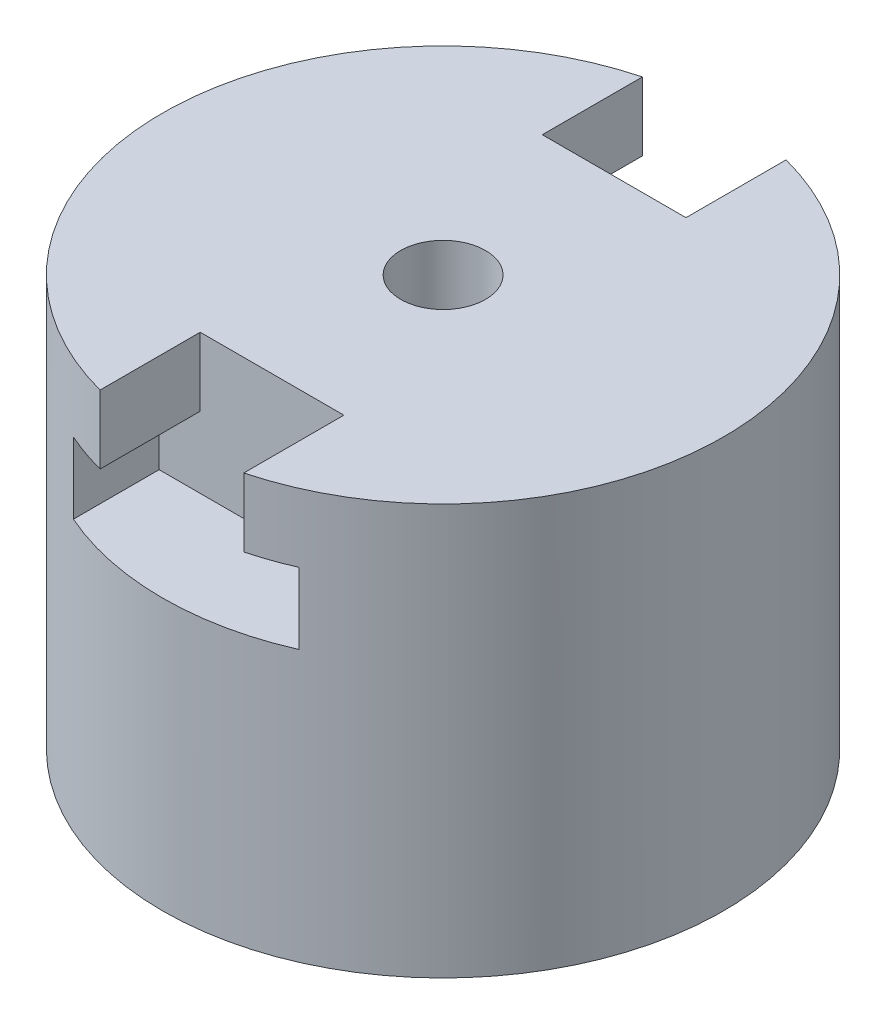
SolidWorks part; units mm, degrees
ref_plane "Front Plane" through (0, 0, 0) normal (0, 0, 1) x (1, 0, 0)
ref_plane "Top Plane" through (0, 0, 0) normal (0, 1, 0) x (1, 0, 0)
ref_plane "Right Plane" through (0, 0, 0) normal (1, 0, 0) x (0, 0, -1)
sketch "Sketch2" plane through (0, 0, 0) normal (0, 1, 0) x (1, 0, 0)
  circle A0 centre (0, 0) radius 20.5
  dimension "D1" = 41
extrude "Boss-Extrude2" add sketch "Sketch2" along normal blind 30
sketch "Sketch3" plane through (0, 0, 0) normal (0, -1, 0) x (1, 0, 0)
  circle A0 centre (0, 0) radius 11.5
sketch "Sketch4" plane through (0, 0, 0) normal (0, -1, 0) x (1, 0, 0)
  circle A0 centre (0, 0) radius 12
  circle A1 centre (0, 0) radius 15.5
  dimension "D1" = 24
  dimension "D2" = 31
extrude "Cut-Extrude2" cut sketch "Sketch4" against normal blind 5
sketch "Sketch5" plane through (0, 0, 0) normal (0, 0, 1) x (1, 0, 0)
  line L0 (0, 0) -> (0, 11.4472)
  line L1 (0, 11.4472) -> (3.1, 11.4472)
  line L2 (3.1, 11.4472) -> (11.5, 0)
  line L3 (-11.5, 0) -> (11.5, 0) construction
  line L4 (11.5, 0) -> (0, 0)
  dimension "D1" = 3.1
revolve "Cut-Revolve1" cut sketch "Sketch5" angle 360 about L0
sketch "Sketch6" plane through (0, 11.4472, 0) normal (0, -1, 0) x (1, 0, 0)
  circle A0 centre (0, 0) radius 3.1
extrude "Cut-Extrude3" cut sketch "Sketch6" against normal through all
ref_plane "Plane2" through (0, 0, 20.5) normal (0, 0, 1) x (1, 0, 0)
sketch "Sketch8" plane through (0, 0, 20.5) normal (0, 0, 1) x (1, 0, 0)
  line L5 (-5.25, 30) -> (5.25, 30)
  line L6 (-8.25, 25) -> (-8.25, 19.8)
  line L7 (-8.25, 19.8) -> (8.25, 19.8)
  line L8 (8.25, 25) -> (8.25, 19.8)
  line L9 (0, 30) -> (0, 0) construction
  line L13 (-8.25, 25) -> (-5.25, 25)
  line L14 (-5.25, 30) -> (-5.25, 25)
  line L17 (8.25, 25) -> (5.25, 25)
  line L18 (5.25, 30) -> (5.25, 25)
  dimension "D1" = 16.5
  dimension "D3" = 8.25
  dimension "D4" = 3
  dimension "5" = 3
  dimension "D5" = 5
  dimension "D6" = 5
extrude "Cut-Extrude4" cut sketch "Sketch8" against normal blind 8
ref_plane "Plane3" through (0, 0, -20.5) normal (0, 0, 1) x (1, 0, 0)
sketch "Sketch9" plane through (0, 0, -20.5) normal (0, 0, 1) x (1, 0, 0)
  line L1 (5.25, 30) -> (-5.25, 30)
  line L2 (8.25, 25) -> (8.25, 19.8)
  line L3 (8.25, 19.8) -> (-8.25, 19.8)
  line L4 (-8.25, 25) -> (-8.25, 19.8)
  line L5 (0, 30) -> (0, 11.4472) construction
  line L12 (-8.25, 25) -> (-5.25, 25)
  line L13 (-5.25, 30) -> (-5.25, 25)
  line L16 (8.25, 25) -> (5.25, 25)
  line L17 (5.25, 30) -> (5.25, 25)
  dimension "D1" = 8.25
  dimension "D2" = 16.5
  dimension "D4" = 5
  dimension "D5" = 5
  dimension "D6" = 3
  dimension "3" = 3
extrude "Cut-Extrude6" cut sketch "Sketch9" along normal blind 8
